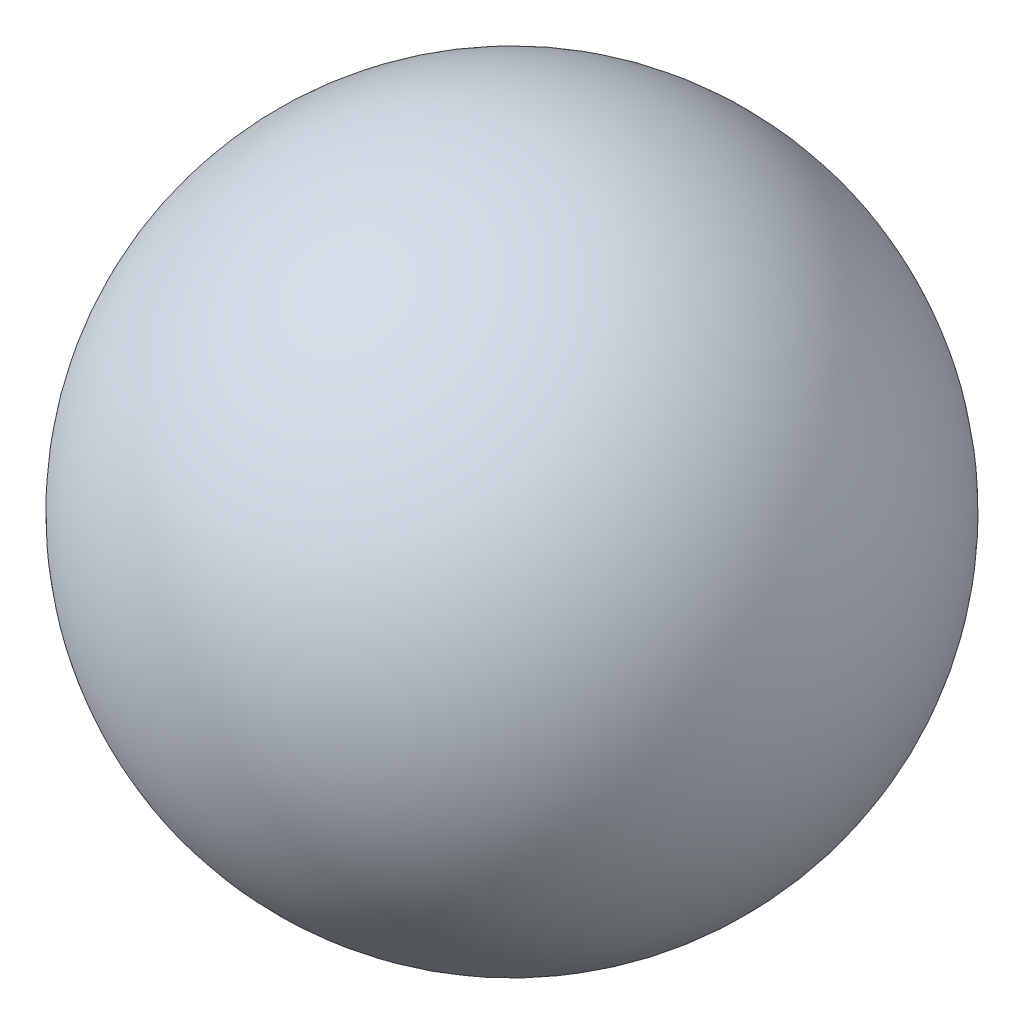
SolidWorks part; units mm, degrees
ref_plane "前视基准面" through (0, 0, 0) normal (0, 0, 1) x (1, 0, 0)
ref_plane "上视基准面" through (0, 0, 0) normal (0, 1, 0) x (1, 0, 0)
ref_plane "右视基准面" through (0, 0, 0) normal (1, 0, 0) x (0, 0, -1)
sketch "草图1" plane through (0, 0, 0) normal (0, 1, 0) x (1, 0, 0)
  line L0 (0, 8) -> (0, -8)
  circle A0 centre (0, 0) radius 8
  dimension "D1" = 16
revolve "旋转1" add sketch "草图1" angle 360 about L0
